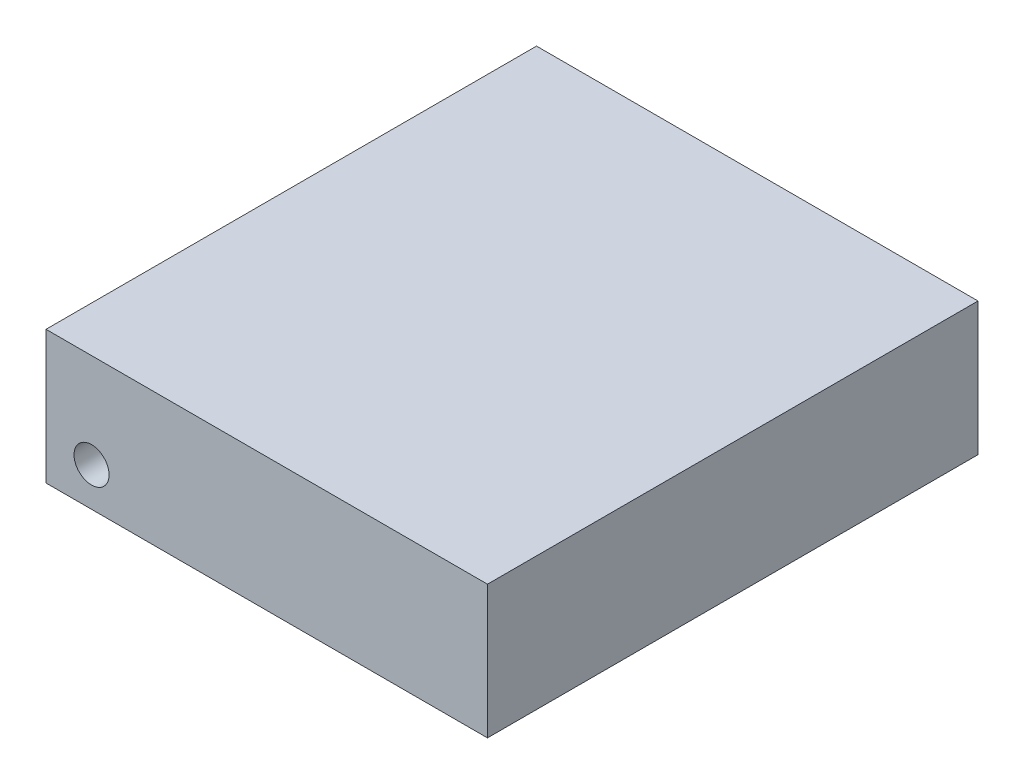
SolidWorks part; units mm, degrees
ref_plane "Front Plane" through (0, 0, 0) normal (0, 0, 1) x (1, 0, 0)
ref_plane "Top Plane" through (0, 0, 0) normal (0, 1, 0) x (1, 0, 0)
ref_plane "Right Plane" through (0, 0, 0) normal (1, 0, 0) x (0, 0, -1)
sketch "Sketch1" plane through (0, 0, 0) normal (0, 1, 0) x (1, 0, 0)
  line L1 (0, 0) -> (63, 0)
  line L2 (0, 0) -> (0, 70)
  line L3 (0, 70) -> (63, 70)
  line L4 (63, 0) -> (63, 70)
  dimension "D1" = 70
  dimension "D2" = 63
extrude "Boss-Extrude1" add sketch "Sketch1" along normal blind 19
sketch "Sketch2" plane through (0, 0, 0) normal (0, 0, 1) x (1, 0, 0)
  line L0 (0, 19) -> (0, 0) construction
  line L1 (0, 0) -> (63, 0) construction
  circle A0 centre (6.5, 5.5) radius 2.5
  dimension "D1" = 5
  dimension "D2" = 6.5
  dimension "D3" = 5.5
extrude "Cut-Extrude1" cut sketch "Sketch2" against normal blind 10
